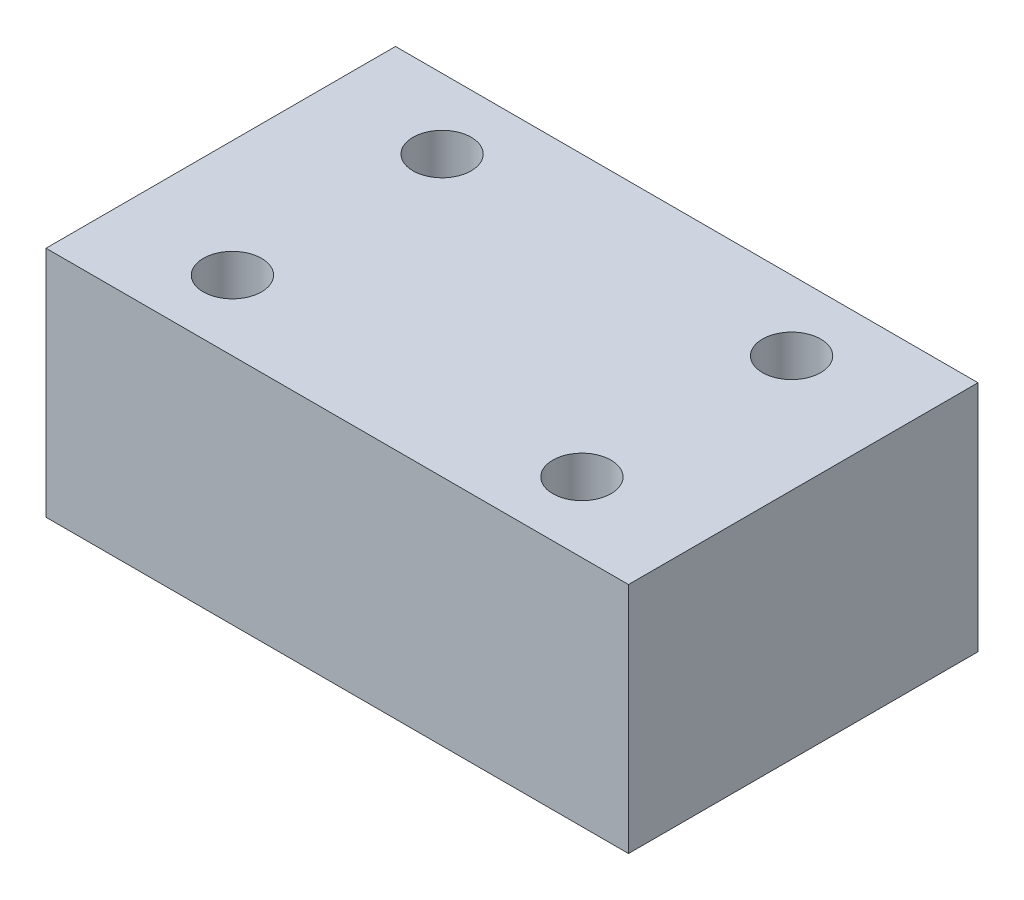
SolidWorks part; units mm, degrees
ref_plane "前视基准面" through (0, 0, 0) normal (0, 0, 1) x (1, 0, 0)
ref_plane "上视基准面" through (0, 0, 0) normal (0, 1, 0) x (1, 0, 0)
ref_plane "右视基准面" through (0, 0, 0) normal (1, 0, 0) x (0, 0, -1)
other "Configuration Table"
sketch "草图1" plane through (0, 0, 0) normal (0, 1, 0) x (1, 0, 0)
  line L1 (-125, -75) -> (125, -75)
  line L2 (-125, -75) -> (-125, 75)
  line L3 (-125, 75) -> (125, 75)
  line L4 (125, -75) -> (125, 75)
  line L5 (-125, -75) -> (125, 75) construction
  line L6 (-125, 75) -> (125, -75) construction
  point P0 (0, 0)
  dimension "D1" = 250
  dimension "D2" = 150
extrude "凸台-拉伸2" add sketch "草图1" along normal blind 100
sketch "草图3" plane through (0, 100, 0) normal (0, 1, 0) x (1, 0, 0)
  line L5 (-75, -45) -> (75, 45) construction
  line L6 (-75, 45) -> (75, -45) construction
  circle A0 centre (-75, 45) radius 12.5
  circle A1 centre (75, 45) radius 12.5
  circle A2 centre (75, -45) radius 12.5
  circle A3 centre (-75, -45) radius 12.5
  point P0 (0, 0)
  dimension "D1" = 150
  dimension "D2" = 90
extrude "切除-拉伸1" cut sketch "草图3" against normal blind 20
